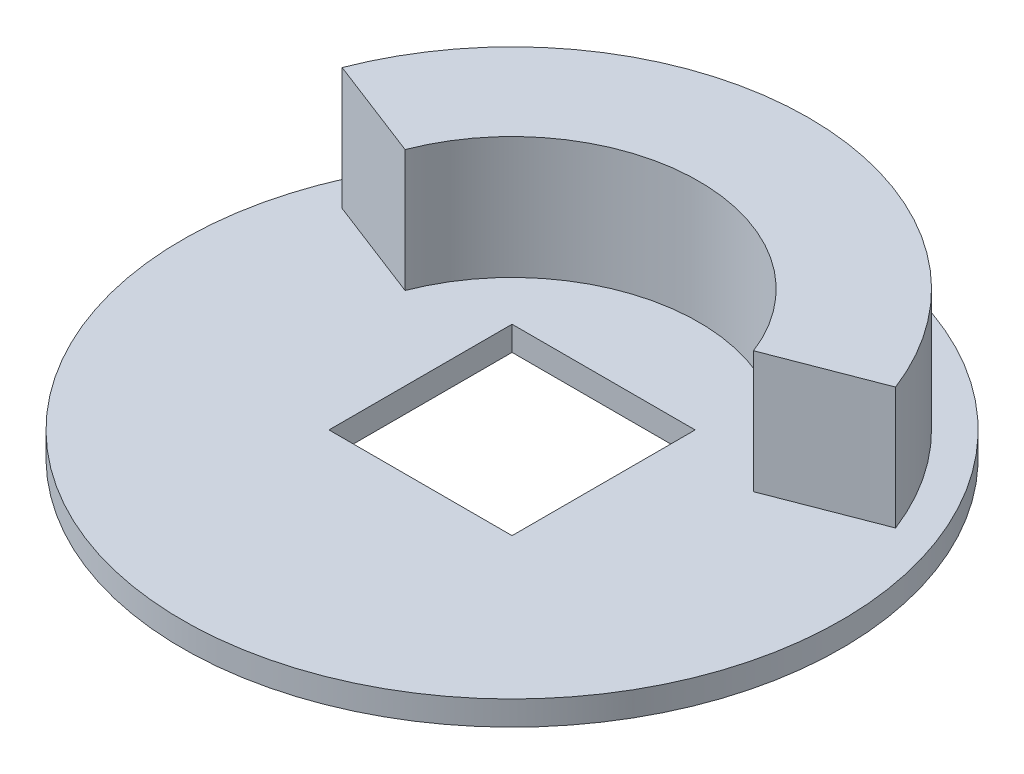
SolidWorks part; units mm, degrees
ref_plane "Front Plane" through (0, 0, 0) normal (0, 0, 1) x (1, 0, 0)
ref_plane "Top Plane" through (0, 0, 0) normal (0, 1, 0) x (1, 0, 0)
ref_plane "Right Plane" through (0, 0, 0) normal (1, 0, 0) x (0, 0, -1)
sketch "Sketch1" plane through (0, 0, 0) normal (0, 1, 0) x (1, 0, 0)
  line L0 (-55, 0) -> (55, 0) construction
  line L1 (-22.6698, 8.7505) -> (-16.656, 24.3305) construction
  line L2 (-22.6698, 8.7505) -> (-14.2736, 5.5095)
  line L3 (0, -55) -> (0, 55) construction
  line L4 (22.6698, 8.7505) -> (14.2736, 5.5095)
  line L5 (-23.78, 5) -> (23.78, 5) construction
  circle A0 centre (0, 0) radius 15.3 construction
  circle A1 centre (0, 0) radius 24.3 construction
  arc A2 (-22.6698, 8.7505) -> (22.6698, 8.7505) centre (0, 0) cw
  arc A3 (-14.2736, 5.5095) -> (14.2736, 5.5095) centre (0, 0) cw
  point P17 (0, 0)
  point P18 (-14.3277, 6.6602)
  point P19 (-14.6935, 5.8087)
  point P20 (-18.4717, 7.13)
  dimension "D1" = 30.6
  dimension "D2" = 48.6
  dimension "D3" = 2.13
  dimension "D4" = 5
extrude "Boss-Extrude1" add sketch "Sketch1" along normal blind 10 contours A2 L4 A3 L2
sketch "Sketch2" plane through (0, 0, 0) normal (0, -1, 0) x (1, 0, 0)
  line L5 (-7.5, -7.5) -> (7.5, 7.5) construction
  line L6 (7.5, -7.5) -> (-7.5, 7.5) construction
  line L18 (-7.5, 7.5) -> (7.5, 7.5)
  line L19 (-7.5, 7.5) -> (-7.5, -7.5)
  line L20 (-7.5, -7.5) -> (7.5, -7.5)
  line L22 (7.5, 7.5) -> (7.5, -7.5)
  circle A1 centre (0, 0) radius 27
  point P1 (0, 0)
  dimension "D1" = 54
  dimension "D2" = 15
extrude "Boss-Extrude2" add sketch "Sketch2" along normal blind 2
